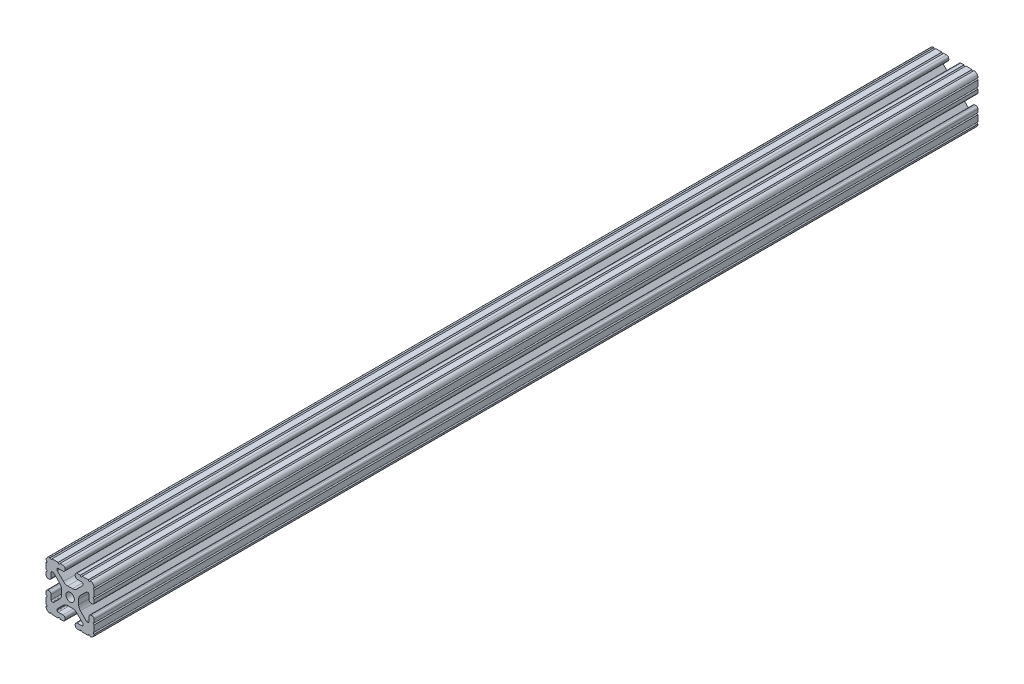
SolidWorks part; units mm, degrees
material "6105-T5 Aluminum"
ref_plane "Front Plane" through (0, 0, 0) normal (0, 0, 1) x (1, 0, 0)
ref_plane "Top Plane" through (0, 0, 0) normal (0, 1, 0) x (1, 0, 0)
ref_plane "Right Plane" through (0, 0, 0) normal (1, 0, 0) x (0, 0, -1)
sketch "Sketch1" plane through (0, 0, 0) normal (0, 0, 1) x (1, 0, 0)
  line L0 (-14.097, 10.287) -> (-13.5289, 10.287)
  line L1 (-12.9003, 10.0266) -> (-8.1292, 5.2555)
  line L2 (-6.738, 1.8969) -> (-6.738, -1.8969)
  line L3 (-8.1292, -5.2555) -> (-12.9003, -10.0266)
  line L4 (-13.5289, -10.287) -> (-14.097, -10.287)
  line L5 (-14.986, -9.398) -> (-14.986, -5.6388)
  line L6 (-16.5608, -4.064) -> (-17.4752, -4.064)
  line L7 (-19.05, -5.6388) -> (-19.05, -7.9756)
  line L8 (-19.05, -9.4996) -> (-19.05, -14.3256)
  line L9 (-19.05, -15.8496) -> (-19.05, -15.875)
  line L10 (-15.875, -19.05) -> (-15.8496, -19.05)
  line L11 (-14.3256, -19.05) -> (-9.4996, -19.05)
  line L12 (-7.9756, -19.05) -> (-5.6388, -19.05)
  line L13 (-4.064, -17.4752) -> (-4.064, -16.5608)
  line L14 (-5.6388, -14.986) -> (-9.398, -14.986)
  line L15 (-10.287, -14.097) -> (-10.287, -13.5289)
  line L16 (-10.0266, -12.9003) -> (-5.2555, -8.1292)
  line L17 (-1.8969, -6.738) -> (1.8969, -6.738)
  line L18 (5.2555, -8.1292) -> (10.0266, -12.9003)
  line L19 (10.287, -13.5289) -> (10.287, -14.097)
  line L20 (9.398, -14.986) -> (5.6388, -14.986)
  line L21 (4.064, -16.5608) -> (4.064, -17.4752)
  line L22 (5.6388, -19.05) -> (7.9756, -19.05)
  line L23 (9.4996, -19.05) -> (14.3256, -19.05)
  line L24 (15.8496, -19.05) -> (15.875, -19.05)
  line L25 (19.05, -15.875) -> (19.05, -15.8496)
  line L26 (19.05, -14.3256) -> (19.05, -9.4996)
  line L27 (19.05, -7.9756) -> (19.05, -5.6388)
  line L28 (17.4752, -4.064) -> (16.5608, -4.064)
  line L29 (14.986, -5.6388) -> (14.986, -9.398)
  line L30 (14.097, -10.287) -> (13.5289, -10.287)
  line L31 (12.9003, -10.0266) -> (8.1292, -5.2555)
  line L32 (6.738, -1.8969) -> (6.738, 1.8969)
  line L33 (8.1292, 5.2555) -> (12.9003, 10.0266)
  line L34 (13.5289, 10.287) -> (14.097, 10.287)
  line L35 (14.986, 9.398) -> (14.986, 5.6388)
  line L36 (16.5608, 4.064) -> (17.4752, 4.064)
  line L37 (19.05, 5.6388) -> (19.05, 7.9756)
  line L38 (19.05, 9.4996) -> (19.05, 14.3256)
  line L39 (19.05, 15.8496) -> (19.05, 15.875)
  line L40 (15.875, 19.05) -> (15.8496, 19.05)
  line L41 (14.3256, 19.05) -> (9.4996, 19.05)
  line L42 (7.9756, 19.05) -> (5.6388, 19.05)
  line L43 (4.064, 17.4752) -> (4.064, 16.5608)
  line L44 (5.6388, 14.986) -> (9.398, 14.986)
  line L45 (10.287, 14.097) -> (10.287, 13.5289)
  line L46 (10.0266, 12.9003) -> (5.2555, 8.1292)
  line L47 (1.8969, 6.738) -> (-1.8969, 6.738)
  line L48 (-5.2555, 8.1292) -> (-10.0266, 12.9003)
  line L49 (-10.287, 13.5289) -> (-10.287, 14.097)
  line L50 (-9.398, 14.986) -> (-5.6388, 14.986)
  line L51 (-4.064, 16.5608) -> (-4.064, 17.4752)
  line L52 (-5.6388, 19.05) -> (-7.9756, 19.05)
  line L53 (-9.4996, 19.05) -> (-14.3256, 19.05)
  line L54 (-15.8496, 19.05) -> (-15.875, 19.05)
  line L55 (-19.05, 15.875) -> (-19.05, 15.8496)
  line L56 (-19.05, 14.3256) -> (-19.05, 9.4996)
  line L57 (-19.05, 7.9756) -> (-19.05, 5.6388)
  line L58 (-17.4752, 4.064) -> (-16.5608, 4.064)
  line L59 (-14.986, 5.6388) -> (-14.986, 9.398)
  circle A0 centre (0, 0) radius 3.3274
  arc A1 (-14.097, 10.287) -> (-14.986, 9.398) centre (-14.097, 9.398) ccw
  arc A2 (-12.9003, 10.0266) -> (-13.5289, 10.287) centre (-13.5289, 9.398) ccw
  arc A3 (-6.738, 1.8969) -> (-8.1292, 5.2555) centre (-11.4878, 1.8969) ccw
  arc A4 (-8.1292, -5.2555) -> (-6.738, -1.8969) centre (-11.4878, -1.8969) ccw
  arc A5 (-13.5289, -10.287) -> (-12.9003, -10.0266) centre (-13.5289, -9.398) ccw
  arc A6 (-14.986, -9.398) -> (-14.097, -10.287) centre (-14.097, -9.398) ccw
  arc A7 (-14.986, -5.6388) -> (-16.5608, -4.064) centre (-16.5608, -5.6388) ccw
  arc A8 (-17.4752, -4.064) -> (-19.05, -5.6388) centre (-17.4752, -5.6388) ccw
  arc A9 (-19.05, -9.4996) -> (-19.05, -7.9756) centre (-19.05, -8.7376) ccw
  arc A10 (-19.05, -15.8496) -> (-19.05, -14.3256) centre (-19.05, -15.0876) ccw
  arc A11 (-19.05, -15.875) -> (-15.875, -19.05) centre (-15.875, -15.875) ccw
  arc A12 (-14.3256, -19.05) -> (-15.8496, -19.05) centre (-15.0876, -19.05) ccw
  arc A13 (-7.9756, -19.05) -> (-9.4996, -19.05) centre (-8.7376, -19.05) ccw
  arc A14 (-5.6388, -19.05) -> (-4.064, -17.4752) centre (-5.6388, -17.4752) ccw
  arc A15 (-4.064, -16.5608) -> (-5.6388, -14.986) centre (-5.6388, -16.5608) ccw
  arc A16 (-10.287, -14.097) -> (-9.398, -14.986) centre (-9.398, -14.097) ccw
  arc A17 (-10.0266, -12.9003) -> (-10.287, -13.5289) centre (-9.398, -13.5289) ccw
  arc A18 (-1.8969, -6.738) -> (-5.2555, -8.1292) centre (-1.8969, -11.4878) ccw
  arc A19 (5.2555, -8.1292) -> (1.8969, -6.738) centre (1.8969, -11.4878) ccw
  arc A20 (10.287, -13.5289) -> (10.0266, -12.9003) centre (9.398, -13.5289) ccw
  arc A21 (9.398, -14.986) -> (10.287, -14.097) centre (9.398, -14.097) ccw
  arc A22 (5.6388, -14.986) -> (4.064, -16.5608) centre (5.6388, -16.5608) ccw
  arc A23 (4.064, -17.4752) -> (5.6388, -19.05) centre (5.6388, -17.4752) ccw
  arc A24 (9.4996, -19.05) -> (7.9756, -19.05) centre (8.7376, -19.05) ccw
  arc A25 (15.8496, -19.05) -> (14.3256, -19.05) centre (15.0876, -19.05) ccw
  arc A26 (15.875, -19.05) -> (19.05, -15.875) centre (15.875, -15.875) ccw
  arc A27 (19.05, -14.3256) -> (19.05, -15.8496) centre (19.05, -15.0876) ccw
  arc A28 (19.05, -7.9756) -> (19.05, -9.4996) centre (19.05, -8.7376) ccw
  arc A29 (19.05, -5.6388) -> (17.4752, -4.064) centre (17.4752, -5.6388) ccw
  arc A30 (16.5608, -4.064) -> (14.986, -5.6388) centre (16.5608, -5.6388) ccw
  arc A31 (14.097, -10.287) -> (14.986, -9.398) centre (14.097, -9.398) ccw
  arc A32 (12.9003, -10.0266) -> (13.5289, -10.287) centre (13.5289, -9.398) ccw
  arc A33 (6.738, -1.8969) -> (8.1292, -5.2555) centre (11.4878, -1.8969) ccw
  arc A34 (8.1292, 5.2555) -> (6.738, 1.8969) centre (11.4878, 1.8969) ccw
  arc A35 (13.5289, 10.287) -> (12.9003, 10.0266) centre (13.5289, 9.398) ccw
  arc A36 (14.986, 9.398) -> (14.097, 10.287) centre (14.097, 9.398) ccw
  arc A37 (14.986, 5.6388) -> (16.5608, 4.064) centre (16.5608, 5.6388) ccw
  arc A38 (17.4752, 4.064) -> (19.05, 5.6388) centre (17.4752, 5.6388) ccw
  arc A39 (19.05, 9.4996) -> (19.05, 7.9756) centre (19.05, 8.7376) ccw
  arc A40 (19.05, 15.8496) -> (19.05, 14.3256) centre (19.05, 15.0876) ccw
  arc A41 (19.05, 15.875) -> (15.875, 19.05) centre (15.875, 15.875) ccw
  arc A42 (14.3256, 19.05) -> (15.8496, 19.05) centre (15.0876, 19.05) ccw
  arc A43 (7.9756, 19.05) -> (9.4996, 19.05) centre (8.7376, 19.05) ccw
  arc A44 (5.6388, 19.05) -> (4.064, 17.4752) centre (5.6388, 17.4752) ccw
  arc A45 (4.064, 16.5608) -> (5.6388, 14.986) centre (5.6388, 16.5608) ccw
  arc A46 (10.287, 14.097) -> (9.398, 14.986) centre (9.398, 14.097) ccw
  arc A47 (10.0266, 12.9003) -> (10.287, 13.5289) centre (9.398, 13.5289) ccw
  arc A48 (1.8969, 6.738) -> (5.2555, 8.1292) centre (1.8969, 11.4878) ccw
  arc A49 (-5.2555, 8.1292) -> (-1.8969, 6.738) centre (-1.8969, 11.4878) ccw
  arc A50 (-10.287, 13.5289) -> (-10.0266, 12.9003) centre (-9.398, 13.5289) ccw
  arc A51 (-9.398, 14.986) -> (-10.287, 14.097) centre (-9.398, 14.097) ccw
  arc A52 (-5.6388, 14.986) -> (-4.064, 16.5608) centre (-5.6388, 16.5608) ccw
  arc A53 (-4.064, 17.4752) -> (-5.6388, 19.05) centre (-5.6388, 17.4752) ccw
  arc A54 (-9.4996, 19.05) -> (-7.9756, 19.05) centre (-8.7376, 19.05) ccw
  arc A55 (-15.8496, 19.05) -> (-14.3256, 19.05) centre (-15.0876, 19.05) ccw
  arc A56 (-15.875, 19.05) -> (-19.05, 15.875) centre (-15.875, 15.875) ccw
  arc A57 (-19.05, 14.3256) -> (-19.05, 15.8496) centre (-19.05, 15.0876) ccw
  arc A58 (-19.05, 7.9756) -> (-19.05, 9.4996) centre (-19.05, 8.7376) ccw
  arc A59 (-19.05, 5.6388) -> (-17.4752, 4.064) centre (-17.4752, 5.6388) ccw
  arc A60 (-16.5608, 4.064) -> (-14.986, 5.6388) centre (-16.5608, 5.6388) ccw
extrude "Boss-Extrude1" add sketch "Sketch1" along normal blind 698.5
